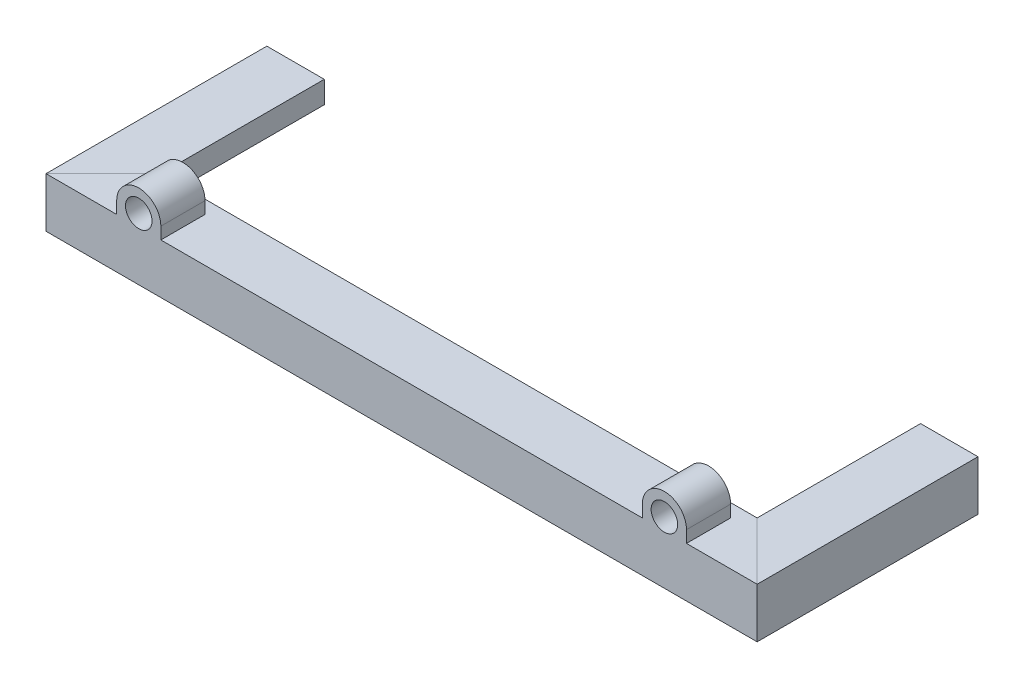
SolidWorks part; units mm, degrees
ref_plane "Alzado" through (0, 0, 0) normal (0, 0, 1) x (1, 0, 0)
ref_plane "Planta" through (0, 0, 0) normal (0, 1, 0) x (1, 0, 0)
ref_plane "Vista lateral" through (0, 0, 0) normal (1, 0, 0) x (0, 0, -1)
sketch "Croquis1" plane through (0, 0, 0) normal (0, 0, 1) x (1, 0, 0)
  line L0 (0, 0) -> (0, 11.3)
  line L1 (0, 11.3) -> (13, 11.3)
  line L2 (13, 11.3) -> (13, 6.3)
  line L3 (13, 6.3) -> (5, 6.3)
  line L4 (5, 6.3) -> (5, 0)
  line L5 (5, 0) -> (0, 0)
  dimension "D1" = 6.3
  dimension "D2" = 5
  dimension "D3" = 8
  dimension "D4" = 5
sketch "Croquis3" plane through (0, 0, 0) normal (0, 1, 0) x (1, 0, 0)
  line L0 (0, 0) -> (0, -50)
  line L1 (0, -50) -> (161, -50)
  line L2 (161, -50) -> (161, 0)
  dimension "D1" = 50
  dimension "D2" = 161
  dimension "D3" = 50
sweep "Barrer1" add profiles "Croquis1" path "Croquis3"
ref_plane "Plano1" through (80.5, 0, 0) normal (1, 0, 0) x (0, 0, -1)
ref_plane "Plano2" through (0, 0, 50) normal (0, 0, 1) x (1, 0, 0)
sketch "Croquis4" plane through (0, 0, 50) normal (0, 0, 1) x (1, 0, 0)
  line L0 (0, 11.3) -> (161, 11.3) construction
  line L1 (16, 11.3) -> (26, 11.3)
  line L2 (16, 11.3) -> (16, 14)
  line L4 (26, 11.3) -> (26, 14)
  line L5 (0, 11.3) -> (0, 0) construction
  arc A0 (26, 14) -> (16, 14) centre (21, 14) ccw
  dimension "D1" = 2.7
  dimension "D2" = 10
  dimension "D3" = 21
extrude "Saliente-Extruir1" add sketch "Croquis4" against normal blind 10
sketch "Croquis7" plane through (0, 0, 50) normal (0, 0, 1) x (1, 0, 0)
  line L0 (161, 11.3) -> (161, 0) construction
  line L1 (0, 11.3) -> (161, 11.3)
  line L2 (0, 11.3) -> (0, 0)
  line L3 (0, 0) -> (161, 0)
  line L4 (161, 11.3) -> (161, 0)
  line L5 (0, 0) -> (161, 0) construction
extrude "Saliente-Extruir3" [suppressed] add sketch "Croquis7" along normal blind 4
sketch "Croquis5" plane through (0, 0, 50) normal (0, 0, 1) x (1, 0, 0)
  circle A0 centre (21, 14) radius 3
  dimension "D1" = 6
extrude "Cortar-Extruir1" cut sketch "Croquis5" against normal through all
mirror "Simetría1" about plane through (80.5, 0, 0) normal (1, 0, 0) of "Cortar-Extruir1", "Saliente-Extruir1"
sketch "Croquis6" plane through (0, 0, 45) normal (0, 0, -1) x (-1, 0, 0)
  line L4 (-5, 6.3) -> (-156, 6.3)
  line L5 (-156, 6.3) -> (-156, 0)
  line L6 (-156, 0) -> (-5, 0)
  line L7 (-5, 0) -> (-5, 6.3)
  line L8 (-5, 6.3) -> (-156, 6.3)
  line L9 (-156, 6.3) -> (-156, 0)
  line L10 (-156, 0) -> (-5, 0)
  line L11 (-5, 0) -> (-5, 6.3)
  dimension "D1" = 0
extrude "Saliente-Extruir2" [suppressed] add sketch "Croquis6" along normal blind 4
